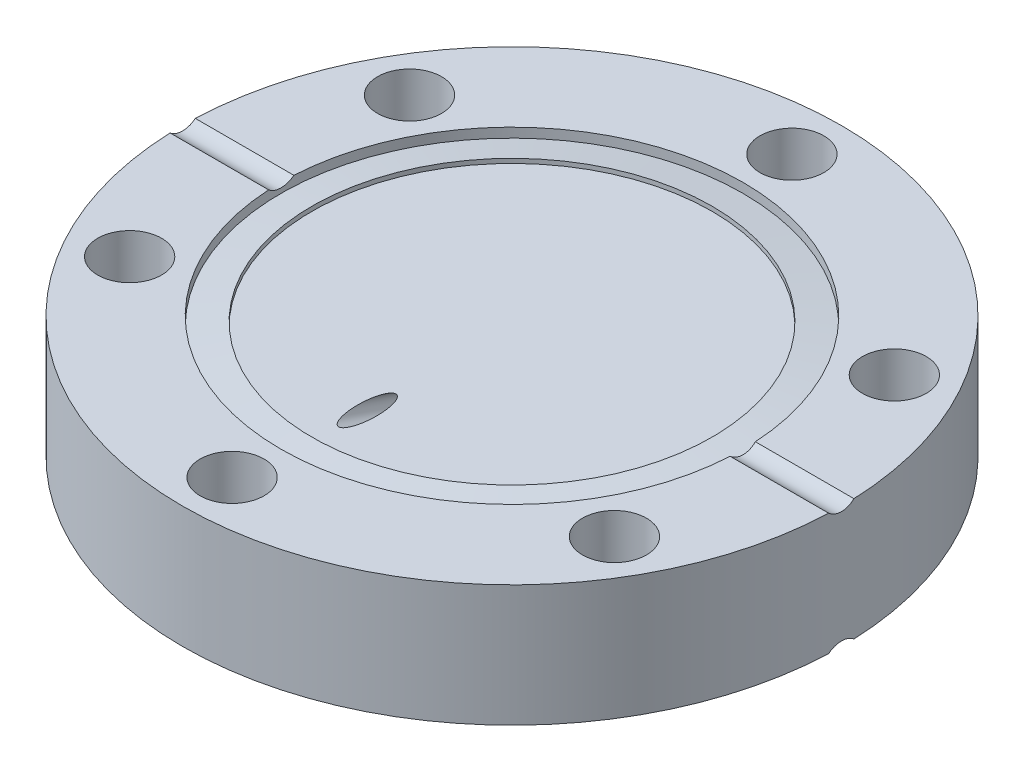
SolidWorks part; units mm, degrees
ref_plane "Front Plane" through (0, 0, 0) normal (0, 0, 1) x (1, 0, 0)
ref_plane "Top Plane" through (0, 0, 0) normal (0, 1, 0) x (1, 0, 0)
ref_plane "Right Plane" through (0, 0, 0) normal (1, 0, 0) x (0, 0, -1)
sketch "Sketch1" plane through (0, 0, 0) normal (0, 1, 0) x (1, 0, 0)
  circle A0 centre (0, 0) radius 34.555
  dimension "D1" = 69.11
extrude "Boss-Extrude1" add sketch "Sketch1" along normal blind 12.75
sketch "Sketch2" plane through (0, 12.75, 0) normal (0, 1, 0) x (1, 0, 0)
  circle A0 centre (0, 29.35) radius 3.35
  dimension "D1" = 6.7
  dimension "D2" = 29.35
extrude "Cut-Extrude1" cut sketch "Sketch2" against normal through all
pattern_circular "CirPattern1" count 6 over 360 about axis through (0, 0, 0) along (0, 1, 0) of "Cut-Extrude1"
sketch "Sketch6" plane through (0, 0, 0) normal (0, -1, 0) x (1, 0, 0)
  circle A0 centre (0, 0) radius 24.23
  dimension "D1" = 48.46
extrude "Cut-Extrude3" cut sketch "Sketch6" against normal blind 1
sketch "Sketch7" plane through (0, 0, 0) normal (1, 0, 0) x (0, 0, -1)
  line L0 (24.23, 1) -> (20.98, 0.5334)
  line L1 (20.98, 0.5334) -> (20.98, 1)
  line L3 (-24.23, 1) -> (24.23, 1) construction
  line L4 (20.98, 1) -> (24.23, 1)
  line L5 (24.23, 0) -> (24.23, 1) construction
  line L7 (0, 0) -> (0, 20.2439) construction
  line L8 (-34.555, 0) -> (34.555, 0) construction
  dimension "D1" = 3.25
  dimension "D2" = 0.5334
revolve "Revolve1" add sketch "Sketch7" angle 360 about L7
ref_plane "Plane1" through (0, 6.375, 0) normal (0, -1, 0) x (1, 0, 0)
mirror "Mirror1" about plane through (0, 6.375, 0) normal (0, -1, 0) of "Cut-Extrude3"
mirror "Mirror2" about plane through (0, 6.375, 0) normal (0, -1, 0) of "Revolve1"
sketch "Sketch4" plane through (0, 0, 0) normal (1, 0, 0) x (0, 0, -1)
  line L0 (0, -1.8729) -> (0, 14.767) construction
  line L3 (34.555, 12.75) -> (-34.555, 12.75) construction
  line L4 (-34.555, 0) -> (34.555, 0) construction
  circle A0 centre (0, 14.25) radius 2
  circle A1 centre (0, -1.5) radius 2
  dimension "D1" = 4
  dimension "D2" = 1.5
  dimension "D3" = 1.5
extrude "Cut-Extrude2" cut sketch "Sketch4" against normal through all and the other way through all
sketch "Sketch8" plane through (0, 6.375, 0) normal (0, -1, 0) x (1, 0, 0)
  line L0 (0, 0) -> (-13.5874, 0) construction
ref_plane "Plane2" through (0, 0.7103, 2.006) normal (0, 0.3338, 0.9426) x (1, 0, 0)
sketch "Sketch9" plane through (0, 0.7103, 2.006) normal (0, 0.3338, 0.9426) x (1, 0, 0)
  line L0 (200000, 6.0093) -> (-200013.5874, 6.0093) construction
  line L1 (0, 6.0093) -> (0, 0) construction
  circle A0 centre (0, 6.0093) radius 1
  dimension "D1" = 2
extrude "Cut-Extrude4" cut sketch "Sketch9" against normal through all and the other way through all
